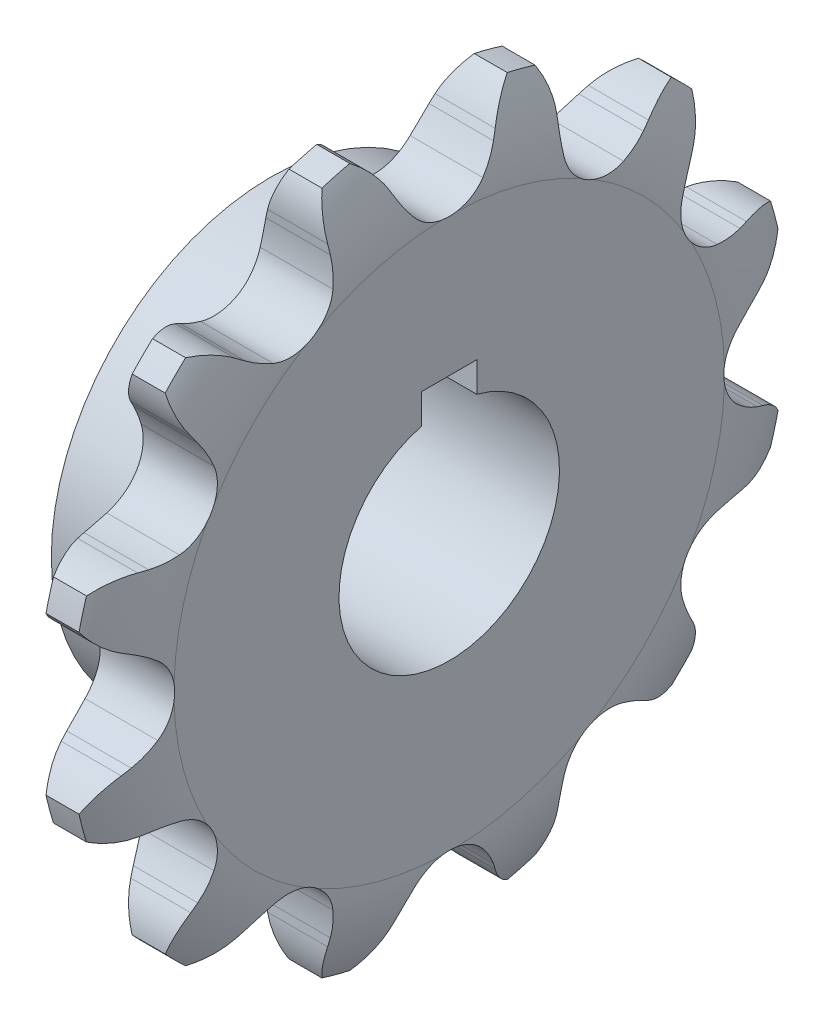
SolidWorks part; units mm, degrees
material "7075-T6 (SN)"
ref_plane "Plane1" through (0, 0, 0) normal (0, 0, 1) x (1, 0, 0)
ref_plane "Plane2" through (0, 0, 0) normal (0, 1, 0) x (1, 0, 0)
ref_plane "Plane3" through (0, 0, 0) normal (1, 0, 0) x (0, 0, -1)
sketch "Clipboard" plane through (0, 0, 0) normal (0, 1, 0) x (1, 0, 0)
  line L0 (0, 0) -> (9.3169, -1.9804)
  line L1 (-15, 0) -> (100, 0) construction
  line L2 (0, 0) -> (-0.7911, 0.8941)
  line L3 (0, 0) -> (-4.4605, 1.7048)
  line L4 (0, 0) -> (4.6709, 0.9928)
  line L5 (0, 0) -> (-9.6384, -3.5949)
  line L6 (0, 0) -> (-3.555, -2.3986)
  line L7 (-0.7911, 0.8941) -> (9.2323, 3.2082)
  line L8 (-76.2, 38.1) -> (-61.976, 38.1)
  line L9 (-73.2057, 38.5609) -> (-73.0533, 38.5634)
  line L10 (-73.0533, 76.1892) -> (-62.9187, 76.1892)
  circle A0 centre (0, 0) radius 2.54
  circle A1 centre (0, 0) radius 12.6304
  circle A2 centre (0, 0) radius 12.7
  dimension "Dr" = 5.08
  dimension "MHD" = 25.2608
  dimension "Hub_dia" = 25.4
  dimension "Num_teeth" = 12
  dimension "Pitch" = 9.525
  dimension "Width" = 4.7752
  dimension "Chamfer_wid" = 1.1938
  dimension "Chamfer_dep" = 4.7752
  dimension "Overall_len" = 10.287
  dimension "Show_teeth" = 12
  dimension "Thickness" = 4.2885
  dimension "OAL" = 10.2871
  dimension "T_dim" = 14.224
  dimension "Width_const" = 0.1524
  dimension "Width_factor" = 0.93
  dimension "Num_strands" = 1
  dimension "Transv_pitch" = 10.1346
sketch "BasProSke" plane through (0, 0, 0) normal (0, 1, 0) x (1, 0, 0)
  line L0 (-10, 0) -> (60, 0) construction
  line L1 (0, 0) -> (0, 15.8562)
  line L2 (0, 0) -> (4.2885, 0)
  line L3 (4.2885, 0) -> (4.2885, 15.8562)
  line L4 (3.0947, 20.6314) -> (1.1938, 20.6314)
  arc A0 (0, 15.8562) -> (1.1938, 20.6314) centre (10.1473, 15.8562) cw
  arc A1 (4.2885, 15.8562) -> (3.0947, 20.6314) centre (-5.8588, 15.8562) ccw
  dimension "D1" = 10.1473
  dimension "G1" = 1.1938
  dimension "G2" = 1.1938
  dimension "H2" = 4.7752
  dimension "Diameter" = 41.2628
  dimension "H1" = 4.7752
  dimension "Thickness" = 4.2885
revolve "Base-Revolve" add sketch "BasProSke" angle 360 about L0
sketch "GrvSke" plane through (0, 0, 0) normal (0, 1, 0) x (1, 0, 0)
  line L0 (4.2885, 15.8562) -> (4.2885, 12.6304)
  line L1 (4.2885, 12.6304) -> (10.1346, 12.6304)
  line L2 (10.1346, 12.6304) -> (10.1346, 15.8562)
  line L3 (3.0947, 20.6314) -> (11.3284, 20.6314)
  line L4 (7.2116, 0) -> (7.2116, 52.07) construction
  line L5 (-10, 0) -> (60, 0) construction
  line L6 (0, 0) -> (35.56, 0) construction
  arc A0 (10.1346, 15.8562) -> (11.3284, 20.6314) centre (20.2819, 15.8562) cw
  arc A1 (4.2885, 15.8562) -> (3.0947, 20.6314) centre (-5.8588, 15.8562) ccw
  dimension "Diameter" = 41.2628
  dimension "H1" = 4.7752
  dimension "Grv_diam" = 25.2608
  dimension "Grv_width" = 5.8461
  dimension "Offset" = 7.2116
  dimension "G1" = 1.1938
revolve "Groove" [suppressed] cut sketch "GrvSke" angle 360 about L6
pattern_linear "Grooves" [suppressed]
sketch "TooCutSke" plane through (0, 0, 0) normal (1, 0, 0) x (0, 0, -1)
  line L0 (2.8337, 18.0265) -> (3.0586, 18.4742)
  line L1 (0, 0) -> (0, 107) construction
  line L2 (0, 18.4009) -> (-10, 18.4009) construction
  line L3 (-2.8337, 18.0265) -> (-3.0586, 18.4742)
  arc A0 (1.9847, 16.7356) -> (2.8337, 18.0265) centre (-3.1132, 21.0132) ccw
  arc A1 (1.9847, 16.7356) -> (-1.9847, 16.7356) centre (0, 18.4009) cw
  arc A2 (3.0586, 18.4742) -> (6.8697, 20.8249) centre (6.8697, 16.5602) cw
  arc A3 (-1.9847, 16.7356) -> (-2.8337, 18.0265) centre (3.1132, 21.0132) cw
  arc A4 (-3.0586, 18.4742) -> (-6.8697, 20.8249) centre (-6.8697, 16.5602) ccw
  arc A5 (6.8697, 20.8249) -> (-6.8697, 20.8249) centre (0, 0) ccw
  dimension "R" = 2.5908
  dimension "E" = 6.6548
  dimension "F" = 4.2647
  dimension "Pitch_radius" = 18.4009
  dimension "W" = 6.8697
  dimension "V" = 1.8407
  dimension "A" = 40
  dimension "B" = 13.333
extrude "ToothCut" cut sketch "TooCutSke" along normal through all
pattern_circular "TeethCuts" count 12 every 30 about axis through (-10, 0, 0) along (1, 0, 0) of "ToothCut"
sketch "HubNeaOneSke" plane through (0, 0, 0) normal (-1, 0, 0) x (0, 0, 1)
  circle A0 centre (0, 0) radius 12.6304
  dimension "Diameter" = 25.2608
extrude "HubNearOne" add sketch "HubNeaOneSke" along normal blind 5.9985
sketch "HubNeaBotSke" plane through (0, 0, 0) normal (-1, 0, 0) x (0, 0, 1)
  circle A0 centre (0, 0) radius 12.6304
  dimension "Diameter" = 25.2608
extrude "HubNearBoth" [suppressed] add sketch "HubNeaBotSke" along normal blind 2.9993
ref_plane "FarPln" through (4.2885, 0, 0) normal (1, 0, 0) x (0, 0, -1)
sketch "HubFarSke" plane through (4.2885, 0, 0) normal (1, 0, 0) x (0, 0, -1)
  circle A0 centre (0, 0) radius 12.6304
  dimension "Diameter" = 25.2608
extrude "HubFar" [suppressed] add sketch "HubFarSke" along normal blind 2.9993
sketch "BorSke" plane through (0, 0, 0) normal (1, 0, 0) x (0, 0, -1)
  circle A0 centre (0, 0) radius 6.35
  dimension "Diameter" = 12.7
extrude "Bore" cut sketch "BorSke" along normal mid plane 20.5741
sketch "KeySke" plane through (0, 0, 0) normal (1, 0, 0) x (0, 0, -1)
  line L0 (-1.5875, 0) -> (-1.5875, 7.874)
  line L1 (-1.5875, 7.874) -> (1.5875, 7.874)
  line L2 (1.5875, 7.874) -> (1.5875, 0)
  line L3 (0, 0) -> (0, 34) construction
  line L4 (-1.5875, 0) -> (1.5875, 0)
  dimension "Offset" = 7.874
  dimension "Width" = 3.175
extrude "Keyway" cut sketch "KeySke" along normal mid plane 20.5741
pattern_circular "Keyway2" [suppressed] count 2 every 90 about axis through (-10, 0, 0) along (1, 0, 0)
equation "\"Num_teeth@Clipboard\" = int( \"Num_teeth@Clipboard\" )"
equation "\"Num_teeth@Clipboard\" = ((sgn( \"Num_teeth@Clipboard\" - 5.0)+1)*( \"Num_teeth@Clipboard\" - 5.0))/2 +5.0"
equation "\"Num_teeth@Clipboard\" = ((sgn( \"Num_teeth@Clipboard\" - 200.0)-1)*( \"Num_teeth@Clipboard\" - 200.0))/-2 +200.0"
equation "\"MHD@Clipboard\" = \"Pitch@Clipboard\" * (1.0 / tan(3.14159265 / \"Num_teeth@Clipboard\" ) - 1.0) - 0.03"
equation "\"Thickness@Clipboard\"  = \"Width@Clipboard\" * \"Width_factor@Clipboard\" - \"Width_const@Clipboard\" + (\"Num_strands@Clipboard\" - 1) * \"Transv_pitch@Clipboard\""
equation "\"OAL@Clipboard\" = \"Thickness@Clipboard\""
equation "\"MHD@Clipboard\" = ((sgn( \"MHD@Clipboard\" - \"Hub_dia@Clipboard\" )-1)*( \"MHD@Clipboard\" - \"Hub_dia@Clipboard\" ))/-2+ \"Hub_dia@Clipboard\""
equation "\"OAL@Clipboard\" = ((sgn( \"OAL@Clipboard\" - \"Overall_len@Clipboard\" )+1)*( \"OAL@Clipboard\" - \"Overall_len@Clipboard\" ))/2 + \"Overall_len@Clipboard\" + 0.000002"
equation "\"Num_teeth@TeethCuts\" = int( \"Show_teeth@Clipboard\" ) + 1"
equation "\"Num_teeth@TeethCuts\" = ((sgn( \"Num_teeth@TeethCuts\" - \"Num_teeth@Clipboard\" )-1)*( \"Num_teeth@TeethCuts\" - \"Num_teeth@Clipboard\" ))/-2+ \"Num_teeth@Clipboard\""
equation "\"Num_teeth@TeethCuts\" = ((sgn( \"Num_teeth@TeethCuts\" - 2.0)+1)*( \"Num_teeth@TeethCuts\" - 2.0))/2 +2.0"
equation "\"Angle@TeethCuts\" = 360.0 / \"Num_teeth@Clipboard\""
equation "\"Pitch_radius@TooCutSke\" = ( \"Pitch@Clipboard\" / 2.0) / sin(3.14159265 / \"Num_teeth@Clipboard\" )  'ma"
equation "\"R@TooCutSke\"  = \"Dr@Clipboard\" * 0.5025 + 0.0015"
equation "\"A@TooCutSke\" = 35.0 + (60.0 / \"Num_teeth@Clipboard\")"
equation "\"E@TooCutSke\"  = \"Dr@Clipboard\" * 1.3025 + 0.0015"
equation "\"B@TooCutSke\"  = 18.0 - (56.0 / \"Num_teeth@Clipboard\" )"
equation "\"W@TooCutSke\" = 1.4 * \"Dr@Clipboard\" * cos(3.14159265 / \"Num_teeth@Clipboard\" )"
equation "\"V@TooCutSke\" = 1.4 * \"Dr@Clipboard\" * sin(3.14159265 / \"Num_teeth@Clipboard\" )"
equation "\"Diameter@BasProSke\" = 2.0 * ( (0.3 * \"Pitch@Clipboard\" ) +  \"Pitch@Clipboard\" / 2.0 / tan(3.14159265 / \"Num_teeth@Clipboard\" ))"
equation "\"Thickness@BasProSke\"  = \"Thickness@Clipboard\""
equation "\"G1@BasProSke\" =  \"Chamfer_wid@Clipboard\""
equation "\"G2@BasProSke\" =  \"Chamfer_wid@Clipboard\""
equation "\"H1@BasProSke\" =  \"Chamfer_dep@Clipboard\""
equation "\"H2@BasProSke\" =  \"Chamfer_dep@Clipboard\""
equation "\"Diameter@GrvSke\" = \"Diameter@BasProSke\""
equation "\"G1@GrvSke\" = \"Chamfer_wid@Clipboard\""
equation "\"H1@GrvSke\" = \"Chamfer_dep@Clipboard\""
equation "\"Grv_diam@GrvSke\" =  \"Pitch@Clipboard\" * (1.0 / tan(3.14159265 / \"Num_teeth@Clipboard\" ) - 1.0) - 0.03"
equation "\"Grv_width@GrvSke\" =  \"Transv_pitch@Clipboard\" - ( \"Width@Clipboard\" * \"Width_factor@Clipboard\" - \"Width_const@Clipboard\" )"
equation "\"Offset@GrvSke\" = \"Grv_width@GrvSke\" / 2.0 + ( \"Width@Clipboard\" * \"Width_factor@Clipboard\" - \"Width_const@Clipboard\" )"
equation "\"Offset@Grooves\" = \"Transv_pitch@Clipboard\""
equation "\"Num_grvs@Grooves\" = \"Num_strands@Clipboard\""
equation "\"Num_grvs@Grooves\" = \"Num_grvs@Grooves\" - 1 * sgn( \"Num_grvs@Grooves\" -1)"
equation "\"Diameter@HubNeaOneSke\" = \"MHD@Clipboard\""
equation "\"Length@HubNearOne\" = \"OAL@Clipboard\" - \"Thickness@BasProSke\""
equation "\"Diameter@HubNeaBotSke\" = \"MHD@Clipboard\""
equation "\"Length@HubNearBoth\" = ( \"OAL@Clipboard\" - \"Thickness@BasProSke\" ) / 2.0"
equation "\"Thickness@FarPln\" = \"Thickness@BasProSke\""
equation "\"Diameter@HubFarSke\" = \"MHD@Clipboard\""
equation "\"Length@HubFar\" = ( \"OAL@Clipboard\" - \"Thickness@BasProSke\" ) / 2.0"
equation "\"D1@Bore\" = \"OAL@Clipboard\" * 2.0"
equation "\"D1@Keyway\" = \"OAL@Clipboard\" * 2.0"
equation "\"Offset@KeySke\" = \"T_dim@Clipboard\" - \"Diameter@BorSke\" / 2.0"
